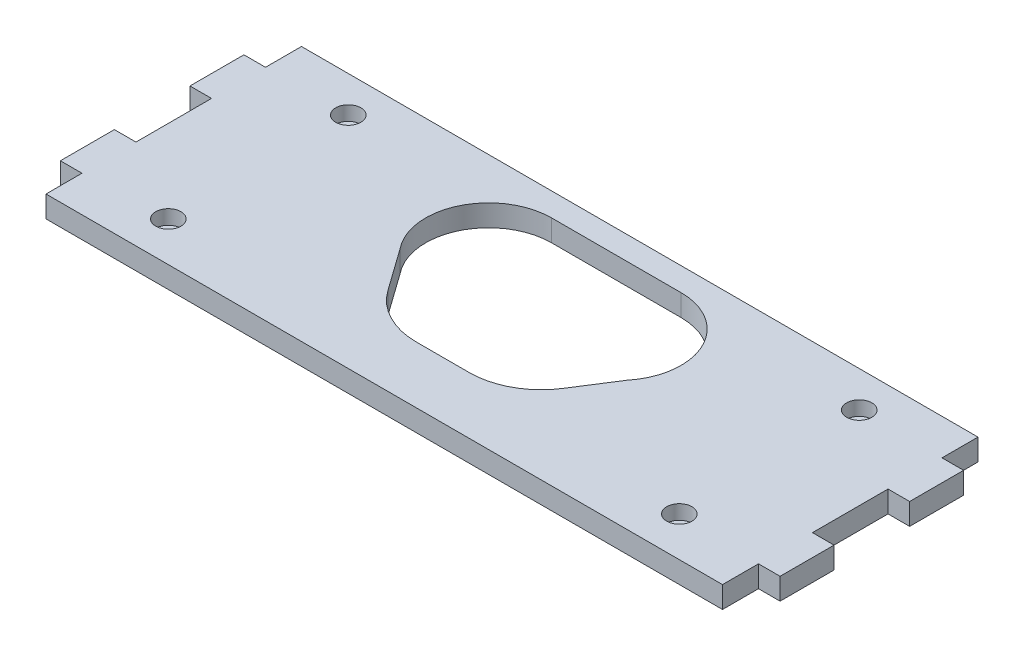
SolidWorks part; units mm, degrees
ref_plane "Plan de face" through (0, 0, 0) normal (0, 0, 1) x (1, 0, 0)
ref_plane "Plan de dessus" through (0, 0, 0) normal (0, 1, 0) x (1, 0, 0)
ref_plane "Plan de droite" through (0, 0, 0) normal (1, 0, 0) x (0, 0, -1)
sketch "Esquisse1" plane through (0, 0, 0) normal (0, 1, 0) x (1, 0, 0)
  line L0 (-94, -35.5) -> (-94, -25.5)
  line L1 (-94, 35.5) -> (94, 35.5)
  line L2 (94, -35.5) -> (94, -25.5)
  line L3 (-94, -35.5) -> (94, -35.5)
  line L4 (-94, -10.5) -> (-94, 10.5)
  line L5 (-94, 35.5) -> (0, 0) construction
  line L6 (0, 0) -> (94, -35.5) construction
  line L7 (-94, -25.5) -> (-100, -25.5)
  line L8 (-94, 25.5) -> (-94, 35.5)
  line L9 (-94, -10.5) -> (-100, -10.5)
  line L10 (94, 35.5) -> (0, 0) construction
  line L11 (-100, -25.5) -> (-100, -10.5)
  line L12 (-94, 25.5) -> (-100, 25.5)
  line L13 (94, -10.5) -> (94, 10.5)
  line L14 (-94, 10.5) -> (-100, 10.5)
  line L15 (-100, 25.5) -> (-100, 10.5)
  line L16 (0, 0) -> (-94, -35.5) construction
  line L17 (94, 25.5) -> (100, 25.5)
  line L18 (0, 0) -> (123.4069, 0) construction
  line L19 (0, 0) -> (-111.2404, 0) construction
  line L21 (94, 10.5) -> (100, 10.5)
  line L22 (100, 25.5) -> (100, 10.5)
  line L23 (94, -25.5) -> (100, -25.5)
  line L24 (94, 25.5) -> (94, 35.5)
  line L25 (94, -10.5) -> (100, -10.5)
  line L26 (100, -25.5) -> (100, -10.5)
  point P0 (0, 0)
  dimension "D1" = 6
  dimension "D2" = 6
  dimension "D3" = 6
  dimension "D4" = 6
  dimension "D5" = 10
  dimension "D6" = 71
  dimension "D7" = 15
  dimension "D8" = 15
  dimension "D9" = 10
  dimension "D10" = 200
  dimension "D11" = 15
  dimension "D12" = 10
  dimension "D13" = 15
  dimension "D14" = 10
extrude "Boss.-Extru.1" add sketch "Esquisse1" along normal blind 6
sketch "Esquisse2" plane through (0, 0, 0) normal (0, -1, 0) x (-1, 0, 0)
  line L0 (0, -35.5) -> (0, 35.5) construction
  line L1 (94, -35.5) -> (-94, -35.5) construction
  line L2 (-94, 35.5) -> (94, 35.5) construction
  line L6 (94, 35.5) -> (94, 25.5) construction
  circle A0 centre (18, 11.5) radius 17.5
  circle A1 centre (71, -24.5) radius 1.65
  circle A2 centre (71, 25.5) radius 1.65
  circle A3 centre (-71, 25.5) radius 1.65
  circle A4 centre (-71, -24.5) radius 1.65
  circle A5 centre (-18, 11.5) radius 17.5
  point P8 (94, 30.5)
  dimension "D1" = 35
  dimension "D4" = 3.3
  dimension "D5" = 3.3
  dimension "D2" = 47
  dimension "D3" = 76
  dimension "D6" = 50
  dimension "D7" = 11
  dimension "D8" = 142
extrude "Enlèv. mat.-Extru.1" cut sketch "Esquisse2" against normal through all
sketch "Esquisse5" plane through (0, 0, 0) normal (0, -1, 0) x (1, 0, 0)
  line L1 (-31.5654, -0.4442) -> (-18, -29)
  line L3 (-18, -29) -> (18, -29)
  line L5 (31.5654, -0.4442) -> (18, -29)
  line L8 (94, -35.5) -> (-94, -35.5) construction
  line L9 (18.7437, 19.6623) -> (31.5654, -0.4442)
  line L10 (18.7437, 19.6623) -> (-17.2563, 19.6623)
  line L12 (-17.2563, 19.6623) -> (-31.5654, -0.4442)
  circle A0 centre (-18, -11.5) radius 17.5 construction
  circle A1 centre (18, -11.5) radius 17.5 construction
  point P0 (0, -11.5)
  dimension "D3" = 6.5
extrude "Enlèv. mat.-Extru.3" cut sketch "Esquisse5" against normal through all
sketch "Esquisse6" plane through (0, 6, 0) normal (0, 1, 0) x (1, 0, 0)
  circle A0 centre (71, -24.5) radius 3.5
  circle A1 centre (71, 25.5) radius 3.5
  circle A2 centre (-71, 25.5) radius 3.5
  circle A3 centre (-71, -24.5) radius 3.5
  dimension "D1" = 7
  dimension "D2" = 7
  dimension "D3" = 7
  dimension "D4" = 7
extrude "Enlèv. mat.-Extru.4" cut sketch "Esquisse6" against normal blind 4
fillet "Congé1" radius 20 2 edges at (18.7437, 3, 19.6623) (-17.2563, 3, 19.6623)
